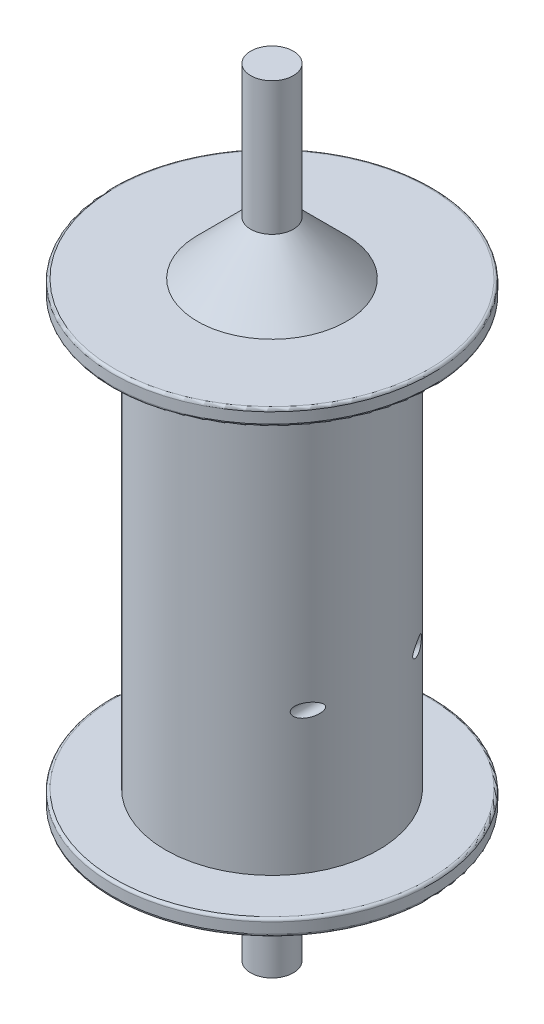
SolidWorks part; units mm, degrees
ref_plane "前视基准面" through (0, 0, 0) normal (0, 0, 1) x (1, 0, 0)
ref_plane "上视基准面" through (0, 0, 0) normal (0, 1, 0) x (1, 0, 0)
ref_plane "右视基准面" through (0, 0, 0) normal (1, 0, 0) x (0, 0, -1)
other "Configuration Table"
sketch "草图1" plane through (0, 0, 0) normal (0, 1, 0) x (1, 0, 0)
  circle A0 centre (0, 0) radius 20
  dimension "D1" = 40
extrude "凸台-拉伸1" add sketch "草图1" along normal blind 80
sketch "草图2" plane through (0, 80, 0) normal (0, 1, 0) x (1, 0, 0)
  circle A0 centre (0, 0) radius 30
  dimension "D1" = 60
extrude "凸台-拉伸2" add sketch "草图2" along normal blind 3
sketch "草图3" plane through (0, 0, 0) normal (0, -1, 0) x (1, 0, 0)
  circle A0 centre (0, 0) radius 30
  dimension "D1" = 60
extrude "凸台-拉伸3" add sketch "草图3" along normal blind 3
sketch "草图4" plane through (0, 0, 0) normal (0, 0, 1) x (1, 0, 0)
  line L0 (30, 0) -> (-30, 0) construction
  circle A0 centre (17, 26.5) radius 1.25
  dimension "D1" = 2.5
  dimension "D2" = 26.5
  dimension "D3" = 17
extrude "切除-拉伸1" cut sketch "草图4" against normal through all both and the other way through all
sketch "草图5" plane through (0, 83, 0) normal (0, 1, 0) x (1, 0, 0)
  circle A0 centre (0, 0) radius 4
  dimension "D1" = 8
fillet "圆角1" radius 0.5 4 edges at (0, 0, -30) (0, 80, 30) (0, 83, 30) (0, -3, -30)
extrude "凸台-拉伸4" add sketch "草图5" along normal blind 35 contours A0
ref_plane "基准面1" through (0, -3, 0) normal (0, -1, 0) x (-1, 0, 0)
sketch "草图6" plane through (0, -3, 0) normal (0, -1, 0) x (-1, 0, 0)
  circle A0 centre (0, 0) radius 4
  dimension "D1" = 8
extrude "凸台-拉伸5" add sketch "草图6" along normal blind 25
chamfer "倒角4" distance 10 angle 45 1 edges at (0, 83, 4)
chamfer "倒角5" distance 10 angle 45 1 edges at (0, -3, -4)
